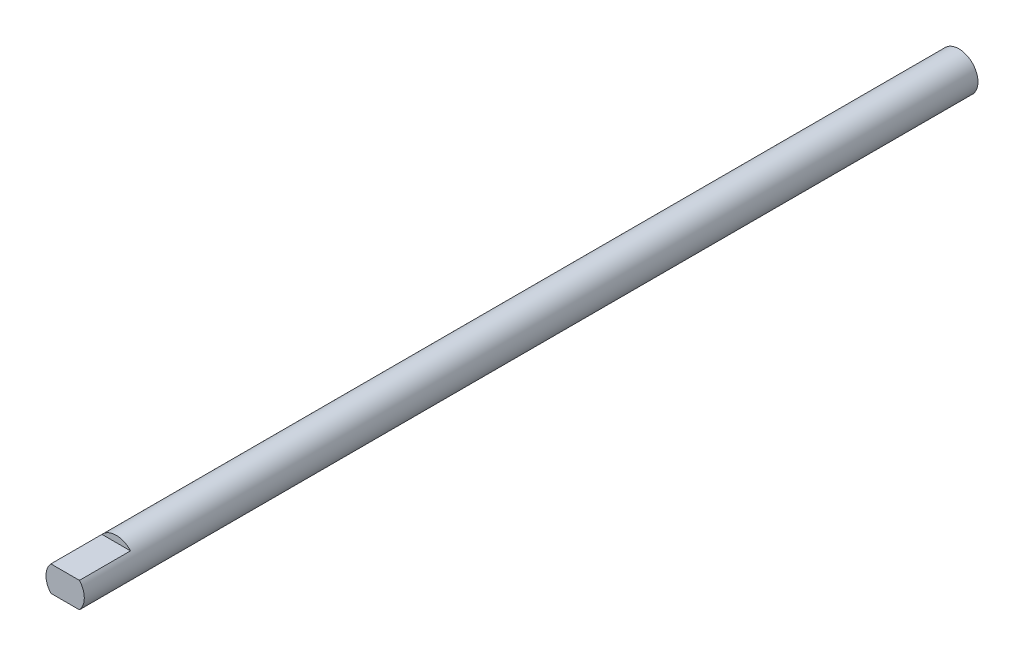
SolidWorks part; units mm, degrees
ref_plane "前视基准面" through (0, 0, 0) normal (0, 0, 1) x (1, 0, 0)
ref_plane "上视基准面" through (0, 0, 0) normal (0, 1, 0) x (1, 0, 0)
ref_plane "右视基准面" through (0, 0, 0) normal (1, 0, 0) x (0, 0, -1)
sketch "草图1" plane through (0, 0, 0) normal (0, 0, 1) x (1, 0, 0)
  circle A0 centre (0, 0) radius 1.5
  dimension "D1" = 3
extrude "凸台-拉伸1" add sketch "草图1" along normal blind 70
sketch "草图2" plane through (0, 0, 70) normal (0, 0, 1) x (1, 0, 0)
  line L0 (0, 0) -> (-1.2062, 0) construction
  line L1 (2.2145, -1) -> (-1.7855, -1)
  line L3 (2.2145, 1) -> (-1.7855, 1)
  line L5 (-1.7855, -1) -> (-1.7855, -2)
  line L6 (-1.7855, 2) -> (2.2145, 2)
  line L7 (-1.7855, 2) -> (-1.7855, 1)
  line L8 (-1.7855, -2) -> (2.2145, -2)
  line L9 (2.2145, 2) -> (2.2145, 1)
  line L10 (2.2145, -1) -> (2.2145, -2)
  dimension "D1" = 2
  dimension "D2" = 4
  dimension "D3" = 1
  dimension "D4" = 1
extrude "切除-拉伸2" cut sketch "草图2" against normal blind 4
